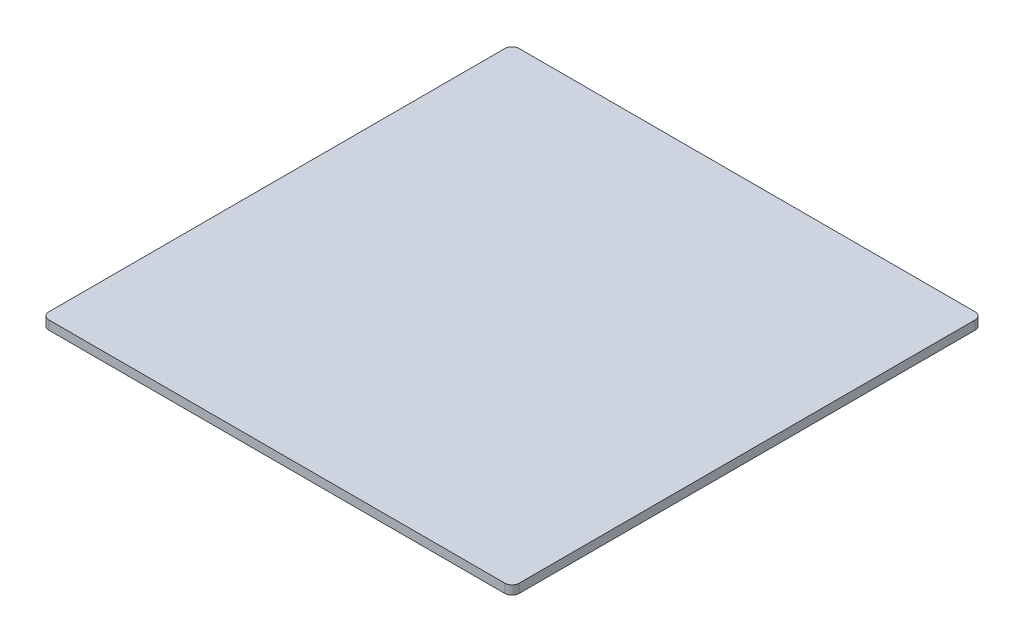
SolidWorks part; units mm, degrees
material "Kapton HN"
ref_plane "Front Plane" through (0, 0, 0) normal (0, 0, 1) x (1, 0, 0)
ref_plane "Top Plane" through (0, 0, 0) normal (0, 1, 0) x (1, 0, 0)
ref_plane "Right Plane" through (0, 0, 0) normal (1, 0, 0) x (0, 0, -1)
sketch "Sketch1" plane through (0, 0, 0) normal (0, 1, 0) x (1, 0, 0)
  line L1 (-50, -50) -> (50, -50)
  line L2 (-50, -50) -> (-50, 50)
  line L3 (-50, 50) -> (50, 50)
  line L4 (50, -50) -> (50, 50)
  line L5 (-50, -50) -> (50, 50) construction
  line L6 (-50, 50) -> (50, -50) construction
  point P0 (0, 0)
  dimension "D1" = 100
extrude "Boss-Extrude1" add sketch "Sketch1" along normal mid plane 1.9
fillet "Fillet1" radius 1.5 4 edges at (-50, 0, 50) (-50, 0, -50) (50, 0, -50) (50, 0, 50)
